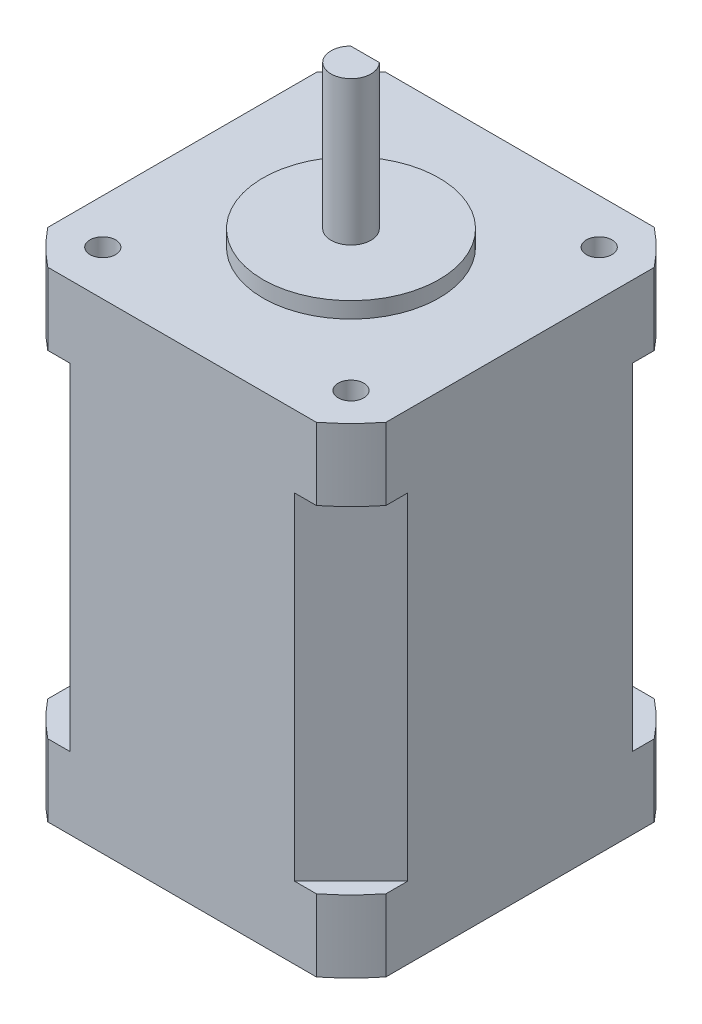
SolidWorks part; units mm, degrees
ref_plane "前视基准面" through (0, 0, 0) normal (0, 0, 1) x (1, 0, 0)
ref_plane "上视基准面" through (0, 0, 0) normal (0, 1, 0) x (1, 0, 0)
ref_plane "右视基准面" through (0, 0, 0) normal (1, 0, 0) x (0, 0, -1)
other "Configuration Table"
sketch "草图2" plane through (0, 0, 0) normal (0, 1, 0) x (1, 0, 0)
  line L0 (-14.0127, 22.4478) -> (-21.0838, 15.3767)
  line L1 (-14.0127, -19.7522) -> (14.0451, -19.7522)
  line L2 (-21.0838, -12.6812) -> (-21.0838, 15.3767)
  line L3 (-14.0127, 22.4478) -> (14.0451, 22.4478)
  line L4 (21.1162, -12.6812) -> (21.1162, 15.3767)
  line L5 (-18.4442, -15.3208) -> (19.9343, 16.5586) construction
  line L6 (-17.2245, 19.2359) -> (15.9664, -17.8309) construction
  line L7 (21.1162, 15.3767) -> (14.0451, 22.4478)
  line L8 (14.0451, -19.7522) -> (21.1162, -12.6812)
  line L9 (-21.0838, -12.6812) -> (-14.0127, -19.7522)
  point P0 (0, 0)
  point P17 (0.0162, 1.3478)
  dimension "D1" = 10
  dimension "D2" = 42.2
  dimension "D3" = 135
  dimension "D5" = 4
extrude "凸台-拉伸1" add sketch "草图2" along normal blind 60
sketch "草图5" plane through (0, 60, 0) normal (0, 1, 0) x (1, 0, 0)
  line L0 (21.1162, -12.6812) -> (21.1162, 15.3767) construction
  line L1 (-16.7762, 22.4478) -> (16.7762, 22.4478)
  line L2 (-21.0838, 18.1444) -> (-21.0838, -15.4488)
  line L3 (-16.7762, -19.7522) -> (16.7762, -19.7522)
  line L4 (21.1162, 18.1036) -> (21.1162, -15.4081)
  line L5 (14.0451, 22.4478) -> (-14.0127, 22.4478) construction
  line L6 (-21.0838, 15.3767) -> (-21.0838, -12.6812) construction
  line L7 (-14.0127, -19.7522) -> (14.0451, -19.7522) construction
  arc A0 (-16.7762, 22.4478) -> (-21.0838, 18.1444) centre (0, 1.3478) ccw
  arc A1 (-21.0838, -15.4488) -> (-16.7762, -19.7522) centre (0, 1.3478) ccw
  arc A2 (16.7762, -19.7522) -> (21.1162, -15.4081) centre (0, 1.3478) ccw
  arc A3 (21.1162, 18.1036) -> (16.7762, 22.4478) centre (0, 1.3478) ccw
  dimension "D1" = 21.1
extrude "凸台-拉伸2" add sketch "草图5" against normal blind 9 contours A3 L1 A0 L2 A1 L3 A2 L4
ref_plane "基准面1" through (0, 30, 0) normal (0, 1, 0) x (1, 0, 0)
mirror "镜向1" about plane through (0, 30, 0) normal (0, 1, 0) of "凸台-拉伸2"
sketch "草图7" plane through (0, 60, 0) normal (0, 1, 0) x (1, 0, 0)
  line L0 (16.7762, 22.4478) -> (-16.7762, 22.4478) construction
  circle A0 centre (0, 1.3478) radius 11
  dimension "D1" = 22
  dimension "D2" = 21.1
extrude "凸台-拉伸3" add sketch "草图7" along normal blind 2
sketch "草图8" plane through (0, 62, 0) normal (0, 1, 0) x (1, 0, 0)
  line L0 (16.7762, 22.4478) -> (-16.7762, 22.4478) construction
  circle A0 centre (0, 1.3478) radius 2.5
  dimension "D1" = 5
  dimension "D2" = 21.1
extrude "凸台-拉伸4" add sketch "草图8" along normal blind 18
sketch "草图9" plane through (0, 80, 0) normal (0, 1, 0) x (1, 0, 0)
  line L0 (-1.7854, 3.0978) -> (1.7854, 3.0978)
  arc A0 (1.7854, 3.0978) -> (-1.7854, 3.0978) centre (0, 1.3478) ccw
  dimension "D1" = 1.75
extrude "切除-拉伸1" cut sketch "草图9" against normal blind 15
sketch "草图10" plane through (0, 60, 0) normal (0, 1, 0) x (1, 0, 0)
  circle A0 centre (-15.5, 16.8478) radius 1.6
  circle A2 centre (15.5, 16.8478) radius 1.6
  circle A3 centre (15.5, -14.1522) radius 1.6
  circle A4 centre (-15.5, -14.1522) radius 1.6
  point P2 (0, 1.3478)
  point P13 (0, 1.3478)
  dimension "D1" = 3.2
  dimension "D2" = 15.5
  dimension "D3" = 15.5
  dimension "D4" = 4
extrude "切除-拉伸2" cut sketch "草图10" against normal blind 4.5
